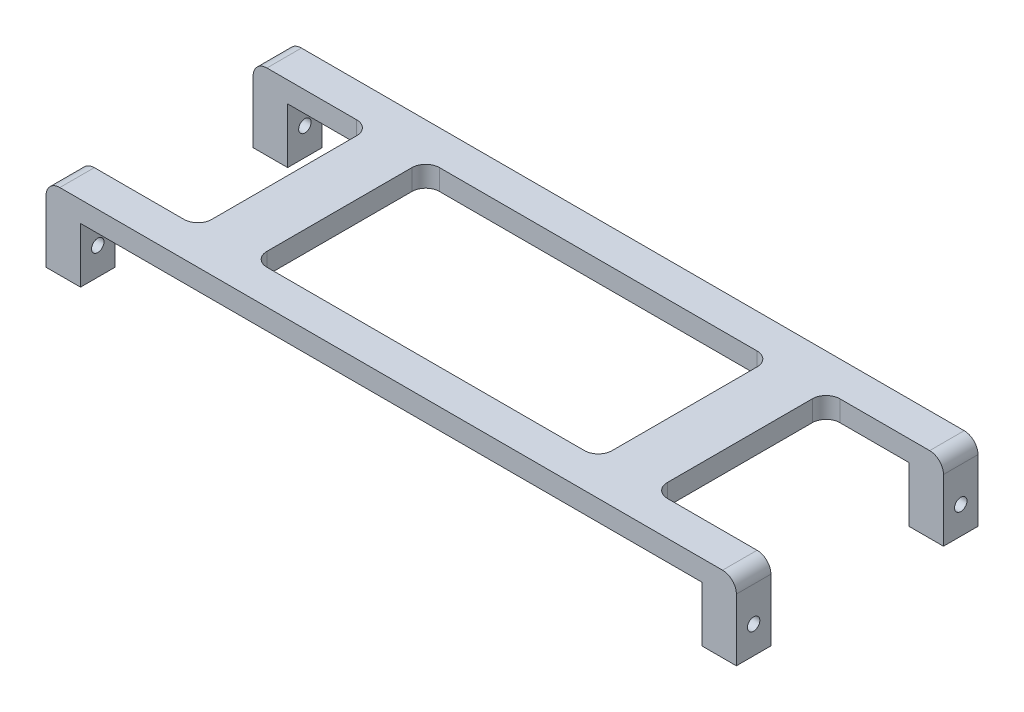
SolidWorks part; units mm, degrees
ref_plane "前视基准面" through (0, 0, 0) normal (0, 0, 1) x (1, 0, 0)
ref_plane "上视基准面" through (0, 0, 0) normal (0, 1, 0) x (1, 0, 0)
ref_plane "右视基准面" through (0, 0, 0) normal (1, 0, 0) x (0, 0, -1)
ref_plane "基准面4" through (0, 0, 0) normal (0, -1, 0) x (1, 0, 0)
sketch "草图1" plane through (0, 0, 0) normal (0, -1, 0) x (1, 0, 0)
  line L0 (50, 17.5) -> (-50, 17.5)
  line L1 (-50, 17.5) -> (-50, -17.5)
  line L2 (-50, -17.5) -> (50, -17.5)
  line L3 (50, -17.5) -> (50, 17.5)
extrude "凸台-拉伸1" add sketch "草图1" against normal blind 3
sketch "草图2" plane through (0, 0, 0) normal (0, -1, 0) x (1, 0, 0)
  line L0 (50, -12.5) -> (50, 12.5)
  line L1 (50, 12.5) -> (33, 12.5)
  line L2 (33, 12.5) -> (33, -12.5)
  line L3 (33, -12.5) -> (50, -12.5)
extrude "切除-拉伸1" cut sketch "草图2" against normal through all
sketch "草图3" plane through (0, 0, 0) normal (0, -1, 0) x (1, 0, 0)
  line L0 (50, -12.5) -> (50, -17.5)
  line L1 (50, -17.5) -> (45, -17.5)
  line L2 (45, -17.5) -> (45, -12.5)
  line L3 (45, -12.5) -> (50, -12.5)
extrude "凸台-拉伸2" add sketch "草图3" along normal blind 8
sketch "草图4" plane through (0, 0, 0) normal (0, -1, 0) x (1, 0, 0)
  line L0 (50, 17.5) -> (50, 12.5)
  line L1 (50, 12.5) -> (45, 12.5)
  line L2 (45, 12.5) -> (45, 17.5)
  line L3 (45, 17.5) -> (50, 17.5)
extrude "凸台-拉伸3" add sketch "草图4" along normal blind 8
sketch "草图5" plane through (0, 0, 0) normal (0, -1, 0) x (1, 0, 0)
  line L0 (-50, -12.5) -> (-33, -12.5)
  line L1 (-33, -12.5) -> (-33, 17.5)
  line L2 (-33, 17.5) -> (-50, 17.5)
  line L3 (-50, 17.5) -> (-50, -12.5)
extrude "切除-拉伸2" cut sketch "草图5" against normal through all
sketch "草图6" plane through (0, 0, 0) normal (0, -1, 0) x (1, 0, 0)
  line L0 (-45, -12.5) -> (-45, -17.5)
  line L1 (-45, -17.5) -> (-50, -17.5)
  line L2 (-50, -17.5) -> (-50, -12.5)
  line L3 (-50, -12.5) -> (-45, -12.5)
extrude "凸台-拉伸4" add sketch "草图6" along normal blind 8
sketch "草图7" plane through (-33, 0, 0) normal (-1, 0, 0) x (0, 0, 1)
  line L0 (12.5, 0) -> (12.5, 3)
  line L1 (12.5, 3) -> (17.5, 3)
  line L2 (17.5, 3) -> (17.5, 0)
  line L3 (17.5, 0) -> (12.5, 0)
extrude "凸台-拉伸5" add sketch "草图7" along normal blind 17
sketch "草图8" plane through (0, 0, 0) normal (0, -1, 0) x (1, 0, 0)
  line L0 (-45, 17.5) -> (-45, 12.5)
  line L1 (-45, 12.5) -> (-50, 12.5)
  line L2 (-50, 12.5) -> (-50, 17.5)
  line L3 (-50, 17.5) -> (-45, 17.5)
extrude "凸台-拉伸6" add sketch "草图8" along normal blind 8
sketch "草图9" plane through (0, 3, 0) normal (0, 1, 0) x (-1, 0, 0)
  line L0 (25, -12.5) -> (25, 12.5)
  line L1 (25, 12.5) -> (-25, 12.5)
  line L2 (-25, 12.5) -> (-25, -12.5)
  line L3 (-25, -12.5) -> (25, -12.5)
extrude "切除-拉伸3" cut sketch "草图9" against normal through all
hole_wizard "Ø1.8 (1.8) 直径孔1" positions "草图11" profile "草图10" hole size "Ø1.8" standard "ANSI Metric"
sketch "草图11" plane through (-50, 0, 0) normal (-1, 0, 0) x (0, 0, 1)
  point P0 (15, -4)
  point P1 (-15, -4)
sketch "草图10" plane through (-50, -4, 15) normal (0, 1, 0) x (0, 0, 1)
  line L0 (0, 0) -> (0, 5)
  line L1 (0, 5) -> (0.9, 5)
  line L2 (0.9, 5) -> (0.9, 0)
  line L5 (0.9, 0) -> (0, 0)
  line L11 (0, -6.35) -> (0, 107.95) construction
  dimension "通孔孔直径" = 1.8
  dimension "通孔孔深度" = 5
hole_wizard "Ø1.8 (1.8) 直径孔2" positions "草图13" profile "草图12" hole size "Ø1.8" standard "ANSI Metric"
sketch "草图13" plane through (50, 0, 0) normal (1, 0, 0) x (0, 0, -1)
  point P0 (15, -4)
  point P1 (-15, -4)
sketch "草图12" plane through (50, -4, -15) normal (0, 1, 0) x (0, 0, -1)
  line L0 (0, 0) -> (0, 100)
  line L1 (0, 100) -> (0.9, 100)
  line L2 (0.9, 100) -> (0.9, 0)
  line L5 (0.9, 0) -> (0, 0)
  line L11 (0, -6.35) -> (0, 107.95) construction
  dimension "通孔孔直径" = 1.8
  dimension "通孔孔深度" = 100
fillet "圆角1" radius 2 12 edges at (33, 1.5, 12.5) (33, 1.5, -12.5) (-33, 1.5, -12.5) (-33, 1.5, 12.5) (-25, 1.5, -12.5) (-25, 1.5, 12.5) (25, 1.5, -12.5) (25, 1.5, 12.5) (50, 3, 15) (50, 3, -15) (-50, 3, 15) (-50, 3, -15)
